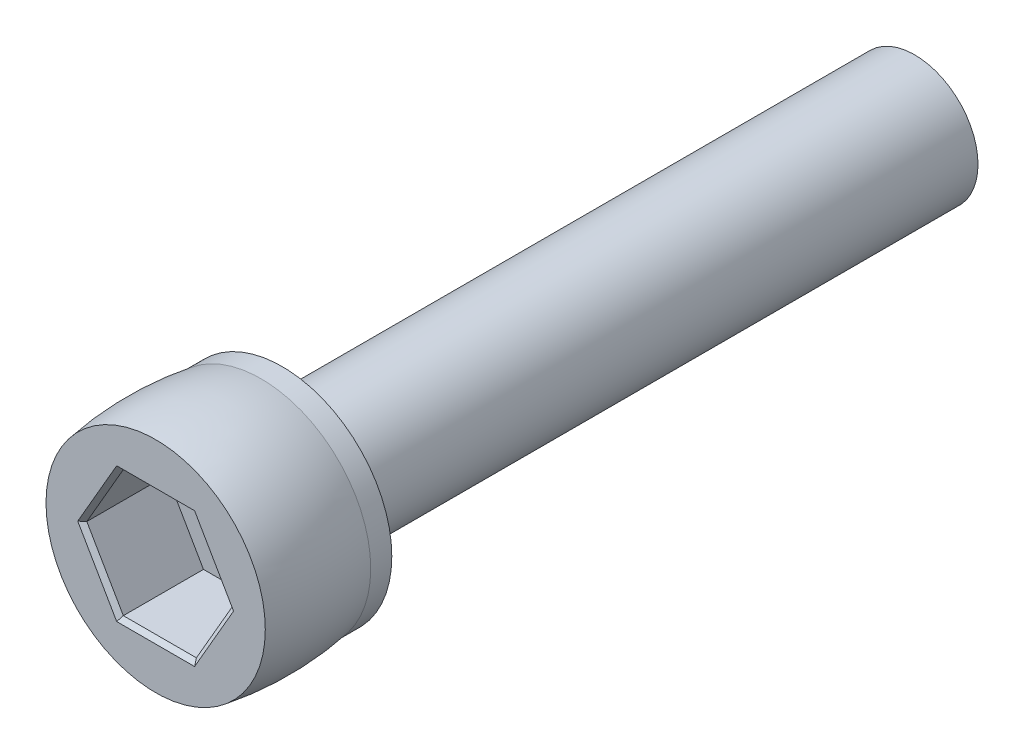
SolidWorks part; units mm, degrees
ref_plane "Front Plane" through (0, 0, 0) normal (0, 0, 1) x (1, 0, 0)
ref_plane "Top Plane" through (0, 0, 0) normal (0, 1, 0) x (1, 0, 0)
ref_plane "Right Plane" through (0, 0, 0) normal (1, 0, 0) x (0, 0, -1)
sketch "Sketch1" plane through (0, 0, 0) normal (0, 0, 1) x (1, 0, 0)
  circle A0 centre (0, 0) radius 1.5
  dimension "D1" = 3
extrude "Boss-Extrude1" add sketch "Sketch1" against normal blind 15
sketch "Sketch2" plane through (0, 0, 0) normal (0, 0, 1) x (1, 0, 0)
  circle A0 centre (0, 0) radius 2.75
  dimension "D1" = 5.5
extrude "Boss-Extrude2" add sketch "Sketch2" along normal blind 3
sketch "Sketch3" plane through (0, 0, 0) normal (1, 0, 0) x (0, 0, -1)
  line L0 (-3, 2.6) -> (-3, 3.1)
  line L1 (-3, 2.75) -> (-3, -2.75) construction
  line L2 (-3, 3.1) -> (0, 3.1)
  line L3 (-0.5, 2.6) -> (0, 2.6)
  line L4 (0, -2.75) -> (0, 2.75) construction
  line L5 (0, 2.6) -> (0, 3.1)
  line L8 (-3, 0) -> (-4.0042, 0)
  arc A1 (-0.5, 2.6) -> (-3, 2.6) centre (-1.75, -5.1625) ccw
  point P4 (0, 0)
  point P8 (0, 0)
  dimension "D1" = 2.6
  dimension "D2" = 0.5
  dimension "D3" = 0.5
  dimension "D4" = 2.6
revolve "Cut-Revolve1" cut sketch "Sketch3" angle 360 about L8
sketch "Sketch4" plane through (0, 0, 3) normal (0, 0, 1) x (1, 0, 0)
  line L1 (1.7321, 0) -> (0.866, 1.5)
  line L2 (0.866, 1.5) -> (-0.866, 1.5)
  line L3 (-0.866, 1.5) -> (-1.7321, 0)
  line L4 (-1.7321, 0) -> (-0.866, -1.5)
  line L5 (-0.866, -1.5) -> (0.866, -1.5)
  line L6 (0.866, -1.5) -> (1.7321, 0)
  circle A0 centre (0, 0) radius 1.5 construction
  dimension "D1" = 3
extrude "Cut-Extrude1" cut sketch "Sketch4" against normal blind 2
chamfer "Chamfer1" distance 0.1 angle 45 6 edges at (-1.299, -0.75, 3) (0, -1.5, 3) (1.299, -0.75, 3) (1.299, 0.75, 3) (0, 1.5, 3) (-1.299, 0.75, 3)
